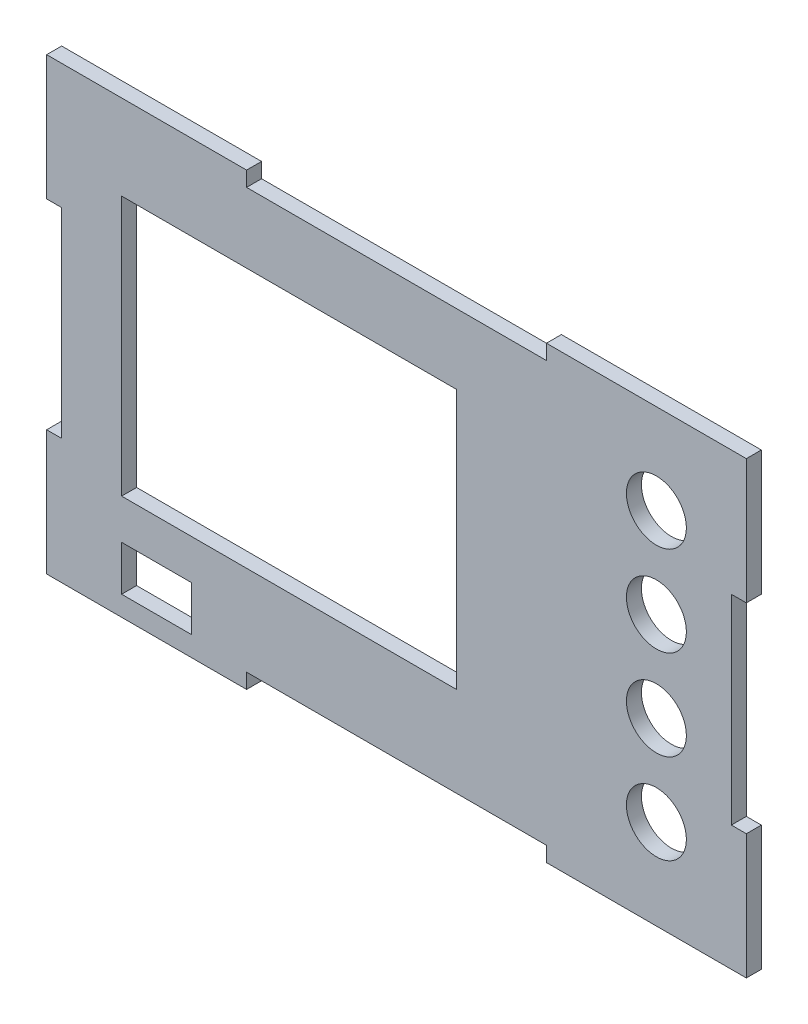
SolidWorks part; units mm, degrees
ref_plane "Спереди" through (0, 0, 0) normal (0, 0, 1) x (1, 0, 0)
ref_plane "Сверху" through (0, 0, 0) normal (0, 1, 0) x (1, 0, 0)
ref_plane "Справа" through (0, 0, 0) normal (1, 0, 0) x (0, 0, -1)
other "Configuration Table"
sketch "Эскиз1" plane through (0, 0, 0) normal (0, 0, 1) x (1, 0, 0)
  line L0 (70, 0) -> (70, 90) construction
  line L1 (0, 0) -> (40, 0)
  line L2 (0, 0) -> (0, 25)
  line L5 (0, 45) -> (140, 45) construction
  line L6 (40, 0) -> (40, 3)
  line L7 (40, 3) -> (100, 3)
  line L8 (137, 25) -> (137, 65)
  line L10 (0, 25) -> (3, 25)
  line L11 (3, 25) -> (3, 65)
  line L12 (140, 25) -> (137, 25)
  line L14 (100, 0) -> (100, 3)
  line L15 (140, 0) -> (140, 25)
  line L16 (140, 0) -> (100, 0)
  line L18 (140, 90) -> (100, 90)
  line L19 (140, 90) -> (140, 65)
  line L20 (100, 90) -> (100, 87)
  line L21 (140, 65) -> (137, 65)
  line L22 (0, 65) -> (3, 65)
  line L23 (40, 87) -> (100, 87)
  line L24 (40, 90) -> (40, 87)
  line L25 (0, 90) -> (0, 65)
  line L26 (0, 90) -> (40, 90)
  point P15 (1.5, 25)
  point P21 (70, 3)
  point P27 (3, 45)
  point P28 (137, 45)
  point P30 (70, 87)
  point P31 (100, 88.5)
  dimension "D1" = 90
  dimension "D2" = 140
  dimension "D3" = 25
  dimension "D4" = 3
  dimension "D5" = 40
  dimension "D6" = 3
  dimension "D7" = 40
  dimension "D8" = 60
extrude "Бобышка-Вытянуть1" add sketch "Эскиз1" along normal blind 3
sketch "Эскиз2" plane through (0, 0, 3) normal (0, 0, 1) x (1, 0, 0)
  line L0 (15, 90) -> (15, 0) construction
  line L1 (40, 90) -> (0, 90) construction
  line L2 (0, 0) -> (40, 0) construction
  line L3 (0, 25) -> (0, 0) construction
  line L4 (15, 4) -> (29, 4)
  line L5 (15, 4) -> (15, 13)
  line L6 (15, 13) -> (29, 13)
  line L7 (29, 4) -> (29, 13)
  dimension "D1" = 9
  dimension "D2" = 14
  dimension "D3" = 4
  dimension "D4" = 15
extrude "Вырез-Вытянуть1" cut sketch "Эскиз2" against normal through all
sketch "Эскиз3" plane through (0, 0, 3) normal (0, 0, 1) x (1, 0, 0)
  line L1 (15, 21) -> (82, 21)
  line L2 (15, 21) -> (15, 73)
  line L3 (15, 73) -> (82, 73)
  line L4 (82, 21) -> (82, 73)
  line L5 (0, 90) -> (0, 65) construction
  line L6 (40, 3) -> (100, 3) construction
  dimension "D1" = 67
  dimension "D2" = 52
  dimension "D3" = 18
  dimension "D4" = 15
extrude "Вырез-Вытянуть2" cut sketch "Эскиз3" against normal through all
sketch "Эскиз4" plane through (0, 0, 3) normal (0, 0, 1) x (1, 0, 0)
  line L0 (140, 65) -> (140, 90) construction
  line L1 (140, 90) -> (100, 90) construction
  circle A0 centre (122, 72) radius 6
  circle A1 centre (122, 54) radius 6
  circle A2 centre (122, 36) radius 6
  circle A3 centre (122, 18) radius 6
  dimension "D1" = 12
  dimension "D2" = 18
  dimension "D3" = 18
  dimension "D5" = 18
  dimension "D4" = 4
extrude "Вырез-Вытянуть3" cut sketch "Эскиз4" against normal through all
